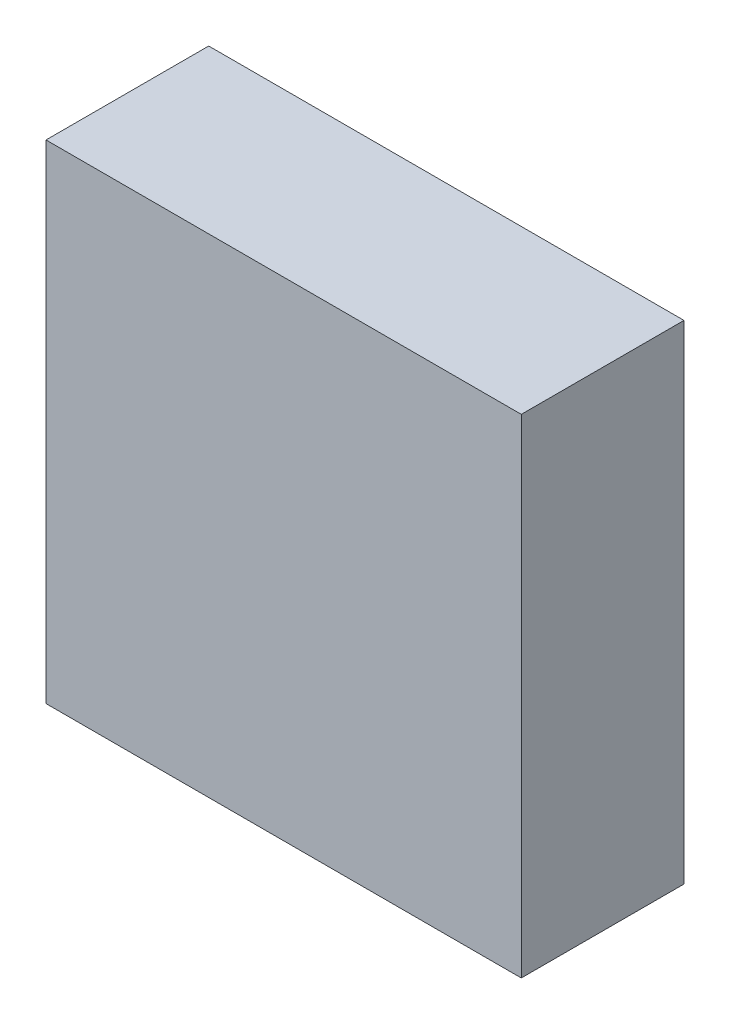
SolidWorks part; units mm, degrees
ref_plane "Front Plane" through (0, 0, 0) normal (0, 0, 1) x (1, 0, 0)
ref_plane "Top Plane" through (0, 0, 0) normal (0, 1, 0) x (1, 0, 0)
ref_plane "Right Plane" through (0, 0, 0) normal (1, 0, 0) x (0, 0, -1)
sketch "Sketch1" plane through (0, 0, 0) normal (0, 0, 1) x (1, 0, 0)
  line L0 (-1.4224, 1.5) -> (1.4986, 1.5)
  line L1 (1.4986, 1.5) -> (1.4986, -1.5)
  line L2 (1.4986, -1.5) -> (-1.4224, -1.5)
  line L3 (-1.4224, -1.5) -> (-1.4224, 1.5)
extrude "Component_Outline" add sketch "Sketch1" along normal blind 1 separate body
sketch3d "3DSketch1"
  line L0 (0, 0, 0) -> (1, 0, 0)
  line L1 (0, 0, 0) -> (0, 1, 0)
  line L2 (0, 0, 0) -> (0, 0, 1)
  point P0 (0, 0, 0)
